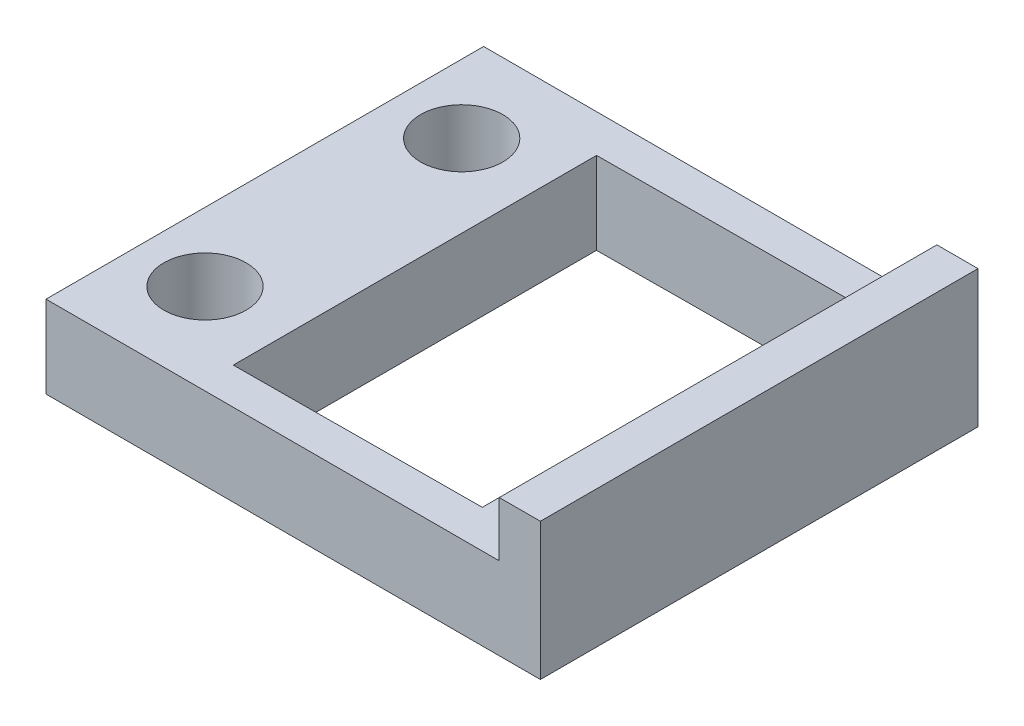
SolidWorks part; units mm, degrees
ref_plane "Front Plane" through (0, 0, 0) normal (0, 0, 1) x (1, 0, 0)
ref_plane "Top Plane" through (0, 0, 0) normal (0, 1, 0) x (1, 0, 0)
ref_plane "Right Plane" through (0, 0, 0) normal (1, 0, 0) x (0, 0, -1)
sketch "Sketch1" plane through (0, 0, 0) normal (0, 1, 0) x (1, 0, 0)
  line L0 (-8.267, 7.9823) -> (-8.267, -7.9823)
  line L1 (-8.267, -7.9823) -> (-3.267, -7.9823)
  line L2 (-2.767, -6.65) -> (-2.767, 6.6)
  line L3 (-3.267, 7.9823) -> (-8.267, 7.9823)
  line L4 (6.267, 6.65) -> (6.267, -6.6)
  line L5 (8.267, -6.6) -> (8.267, 6.6)
  line L6 (-3.267, -7.9823) -> (8.267, -7.9823)
  line L7 (8.267, -7.9823) -> (8.267, -6.6)
  line L8 (6.267, -6.6) -> (-2.767, -6.65)
  line L9 (6.267, 6.65) -> (-2.767, 6.6)
  line L10 (8.267, 6.6) -> (8.267, 7.9823)
  line L11 (8.267, 7.9823) -> (-3.267, 7.9823)
  circle A0 centre (-5.767, 4.6823) radius 1.5
  circle A1 centre (-5.767, -4.6823) radius 1.5
  point P5 (-5.767, 7.9823)
  dimension "D1" = 3
  dimension "D2" = 5
  dimension "D3" = 3.3
  dimension "D4" = 9.3646
  dimension "D5" = 3.3
  dimension "D6" = 2
  dimension "D7" = 3
extrude "Boss-Extrude1" add sketch "Sketch1" along normal blind 3
sketch "Sketch2" plane through (0, 0, 0) normal (0, 1, 0) x (1, 0, 0)
  line L0 (8.267, -7.9823) -> (9.767, -7.9823)
  line L1 (9.767, -7.9823) -> (9.767, 7.9823)
  line L2 (9.767, 7.9823) -> (8.267, 7.9823)
  line L3 (8.267, 7.9823) -> (8.267, -7.9823)
  dimension "D1" = 1.5
extrude "Boss-Extrude2" add sketch "Sketch2" along normal blind 5
